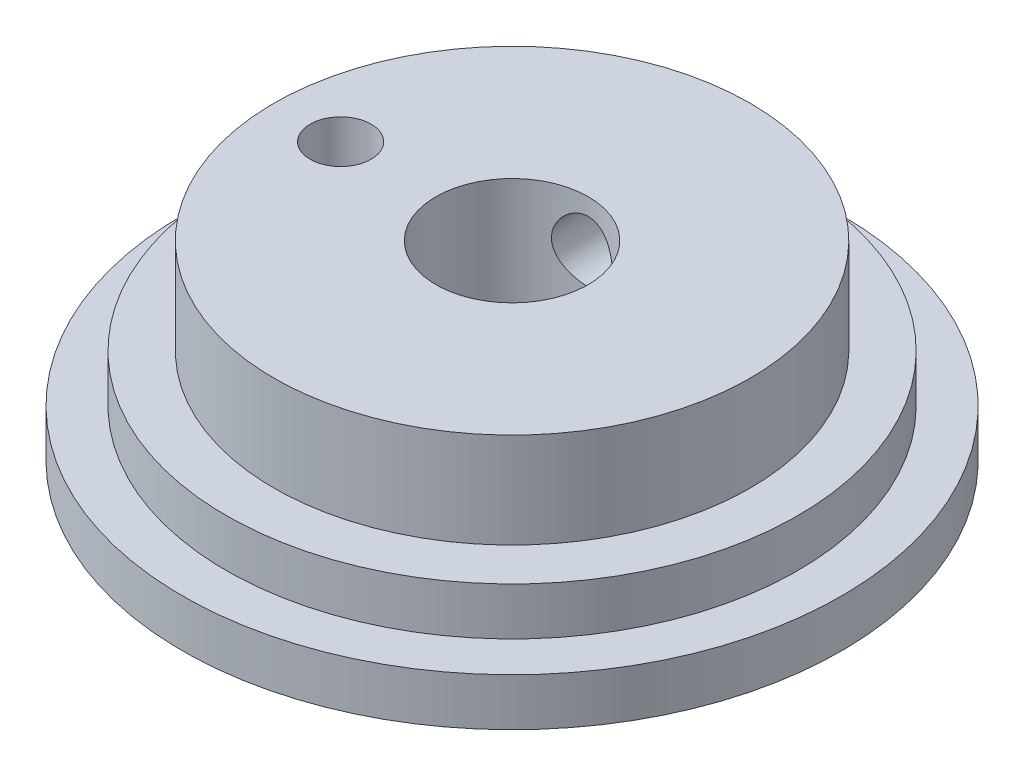
SolidWorks part; units mm, degrees
material "ﾎﾟﾘｴﾁﾚﾝｲﾐﾝ(PEI)"
ref_plane "正面" through (0, 0, 0) normal (0, 0, 1) x (1, 0, 0)
ref_plane "平面" through (0, 0, 0) normal (0, 1, 0) x (1, 0, 0)
ref_plane "右側面" through (0, 0, 0) normal (1, 0, 0) x (0, 0, -1)
sketch "ｽｹｯﾁ1" plane through (0, 0, 0) normal (0, 0, 1) x (1, 0, 0)
  line L0 (0, 0) -> (0, 10) construction
  line L1 (-4, 10) -> (-4, 0)
  line L2 (0, 10) -> (-12.5, 10)
  line L3 (0, 10) -> (0, 5)
  line L4 (0, 5) -> (-12.5, 5)
  line L5 (-12.5, 10) -> (-12.5, 5)
  line L6 (0, 5) -> (-17.3, 5)
  line L7 (0, 5) -> (0, 0)
  line L8 (0, 0) -> (-17.3, 0)
  line L9 (-17.3, 5) -> (-17.3, 0)
  line L10 (-17.3, 5) -> (-15, 5)
  line L11 (-17.3, 5) -> (-17.3, 2.5)
  line L12 (-17.3, 2.5) -> (-15, 2.5)
  line L13 (-15, 5) -> (-15, 2.5)
  dimension "D1" = 5
  dimension "D2" = 5
  dimension "D3" = 17.3
  dimension "D4" = 12.5
  dimension "D5" = 2.3
  dimension "D6" = 2.5
  dimension "D7" = 4
revolve "回転2" add sketch "ｽｹｯﾁ1" angle 360 about L0
sketch "ｽｹｯﾁ2" plane through (0, 0, 0) normal (0, 0, 1) x (1, 0, 0)
  line L0 (0, 10) -> (0, 0) construction
  line L1 (12.5, 10) -> (-12.5, 10) construction
  line L2 (4, 10) -> (-4, 10) construction
  circle A0 centre (0, 7.5) radius 1.6
  dimension "D1" = 3.2
  dimension "D2" = 2.5
extrude "ｶｯﾄ - 押し出し1" cut sketch "ｽｹｯﾁ2" against normal through all
sketch "ｽｹｯﾁ3" plane through (0, 10, 0) normal (0, 1, 0) x (1, 0, 0)
  line L0 (-12.5, 0) -> (12.5, 0) construction
  circle A0 centre (0, 0) radius 12.5 construction
  circle A1 centre (0, 0) radius 12.5 construction
  circle A2 centre (-9, 0) radius 1.6
  circle A3 centre (0, 0) radius 4 construction
  dimension "D1" = 3.2
  dimension "D2" = 9
extrude "ｶｯﾄ - 押し出し2" cut sketch "ｽｹｯﾁ3" against normal through all
